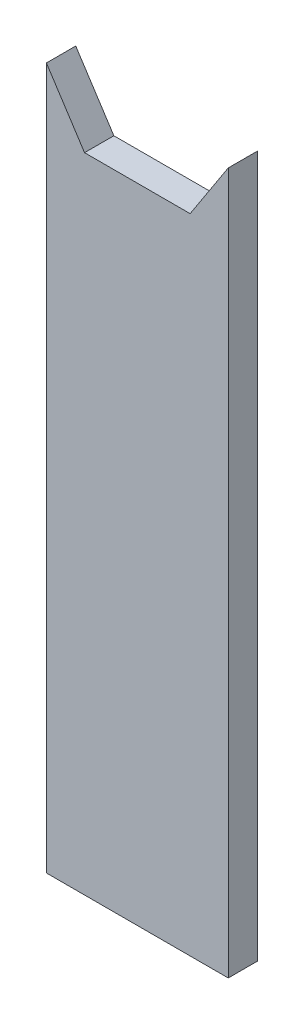
SolidWorks part; units mm, degrees
ref_plane "Front Plane" through (0, 0, 0) normal (0, 0, 1) x (1, 0, 0)
ref_plane "Top Plane" through (0, 0, 0) normal (0, 1, 0) x (1, 0, 0)
ref_plane "Right Plane" through (0, 0, 0) normal (1, 0, 0) x (0, 0, -1)
sketch "Sketch1" plane through (0, 0, 0) normal (0, 0, 1) x (1, 0, 0)
  line L0 (15.5, 109.4043) -> (15.5, -10.1957)
  line L1 (15.5, -10.1957) -> (-15.5, -10.1957)
  line L2 (15.5, 109.4043) -> (9, 99.4043)
  line L3 (9, 99.4043) -> (-9, 99.4043)
  line L4 (0, -11.047) -> (0, 6.688) construction
  line L5 (-15.5, 109.4043) -> (-9, 99.4043)
  line L6 (-15.5, 109.4043) -> (-15.5, -10.1957)
  point P9 (0, 99.4043)
  point P11 (0, -10.1957)
  dimension "D1" = 31
  dimension "D2" = 119.6
  dimension "D3" = 10
  dimension "D4" = 18
extrude "Boss-Extrude1" add sketch "Sketch1" along normal blind 5
